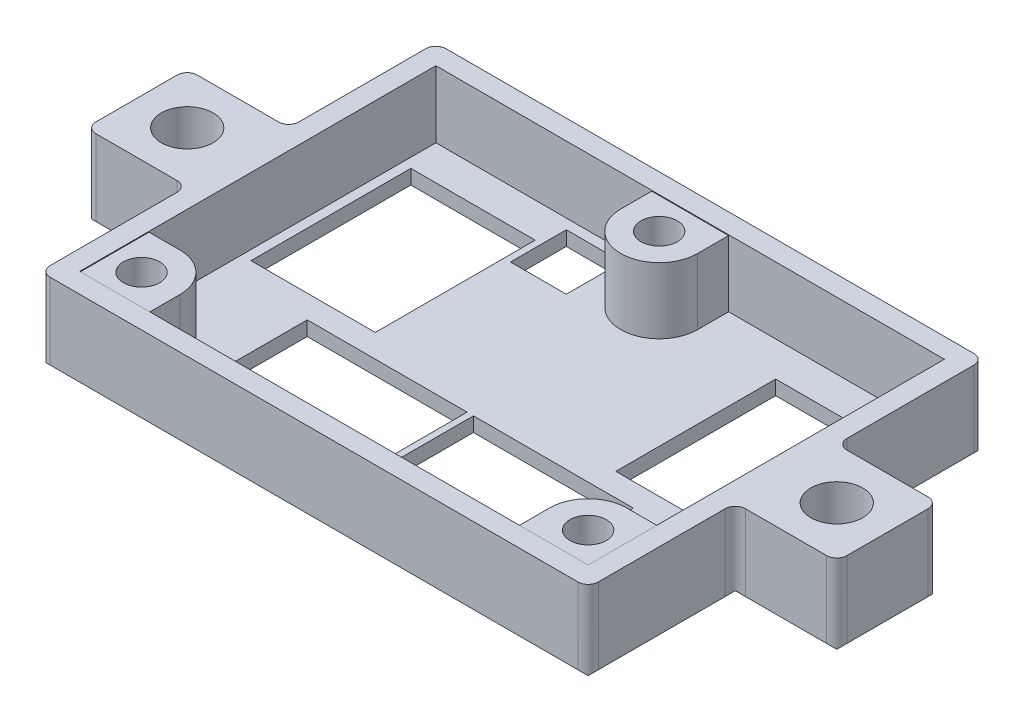
SolidWorks part; units mm, degrees
ref_plane "Front Plane" through (0, 0, 0) normal (0, 0, 1) x (1, 0, 0)
ref_plane "Top Plane" through (0, 0, 0) normal (0, 1, 0) x (1, 0, 0)
ref_plane "Right Plane" through (0, 0, 0) normal (1, 0, 0) x (0, 0, -1)
sketch "Sketch1" plane through (0, 0, 0) normal (0, 1, 0) x (1, 0, 0)
  line L0 (-41.1458, 0) -> (37.3326, 0) construction
  line L1 (-27, -19.5) -> (27, -19.5)
  line L2 (-27, -19.5) -> (-27, 19.5)
  line L3 (-27, 19.5) -> (27, 19.5)
  line L4 (27, -19.5) -> (27, 19.5)
  line L5 (-27, -19.5) -> (27, 19.5) construction
  line L6 (-27, 19.5) -> (27, -19.5) construction
  line L7 (0, 33.589) -> (0, -25.3286) construction
  line L8 (-37, -5) -> (-27, -5)
  line L9 (-37, -5) -> (-37, 5)
  line L10 (-37, 5) -> (-27, 5)
  line L11 (-27, -5) -> (-27, 5)
  line L12 (-37, -5) -> (-27, 5) construction
  line L13 (-37, 5) -> (-27, -5) construction
  line L14 (37, -5) -> (37, 5)
  line L15 (37, 5) -> (27, 5)
  line L16 (37, -5) -> (27, -5)
  circle A0 centre (-32, 0) radius 2.5527
  circle A1 centre (32, 0) radius 2.5527
  point P0 (0, 0)
  point P8 (-32, 0)
  dimension "D5" = 5.1054
  dimension "D1" = 54
  dimension "D2" = 39
  dimension "D3" = 10
  dimension "D4" = 10
extrude "Boss-Extrude1" add sketch "Sketch1" along normal blind 8 contours L1 L4 L3 L2 | L16 L14 L15 L4 A1 | L10 L9 L8 L2 A0
sketch "Sketch2" plane through (0, 8, 0) normal (0, 1, 0) x (1, 0, 0)
  line L0 (0, 27.4) -> (0, -30.8783) construction
  line L1 (-42.9811, 0) -> (41.0645, 0) construction
  line L3 (-25.05, -17.55) -> (25.05, -17.55)
  line L4 (-25.05, -17.55) -> (-25.05, 17.55)
  line L5 (-25.05, 17.55) -> (25.05, 17.55)
  line L6 (25.05, -17.55) -> (25.05, 17.55)
  line L7 (-25.05, -17.55) -> (25.05, 17.55) construction
  line L8 (-25.05, 17.55) -> (25.05, -17.55) construction
  point P5 (0, 0)
  dimension "D1" = 50.1
  dimension "D2" = 35.1
extrude "Cut-Extrude1" cut sketch "Sketch2" against normal blind 0.0762
sketch "Sketch3" plane through (0, 7.9238, 0) normal (0, 1, 0) x (1, 0, 0)
  line L0 (0, 25.6254) -> (0, -24.9156) construction
  line L1 (-43.478, 0) -> (41.2775, 0) construction
  line L2 (-5.4043, 14.5) -> (7.1001, 14.5) construction
  line L3 (-3.79, 14.5) -> (-3.79, 17.55)
  line L4 (25.05, 17.55) -> (-25.05, 17.55) construction
  line L5 (3.79, 14.5) -> (3.79, 17.55)
  line L7 (-22, -6.9215) -> (-22, -24.9156) construction
  line L8 (-15.6235, -14.5) -> (-28.7086, -14.5) construction
  line L9 (-18.21, -14.5) -> (-18.21, -17.55)
  line L10 (-25.05, -17.55) -> (25.05, -17.55) construction
  line L11 (-22, -10.71) -> (-25.05, -10.71)
  line L12 (-25.05, 17.55) -> (-25.05, -17.55) construction
  line L13 (-18.21, -17.55) -> (18.21, -17.55)
  line L14 (-25.05, -10.71) -> (-25.05, 17.55)
  line L15 (-25.05, 17.55) -> (-3.79, 17.55)
  line L16 (18.21, -14.5) -> (18.21, -17.55)
  line L17 (22, -10.71) -> (25.05, -10.71)
  line L18 (25.05, -10.71) -> (25.05, 17.55)
  line L19 (25.05, 17.55) -> (3.79, 17.55)
  arc A0 (-3.79, 14.5) -> (3.79, 14.5) centre (0, 14.5) ccw
  arc A1 (-18.21, -14.5) -> (-22, -10.71) centre (-22, -14.5) ccw
  arc A2 (18.21, -14.5) -> (22, -10.71) centre (22, -14.5) cw
  point P31 (0, -17.55)
  dimension "D1" = 7.58
  dimension "D3" = 7.58
  dimension "D2" = 14.5
  dimension "D4" = 22
  dimension "D5" = 14.5
extrude "Cut-Extrude2" cut sketch "Sketch3" against normal blind 6.5
sketch "Sketch4" plane through (0, 7.9238, 0) normal (0, 1, 0) x (1, 0, 0)
  line L0 (0, 26.0262) -> (0, -25.2956) construction
  line L1 (-42.2713, 0) -> (43.691, 0) construction
  circle A0 centre (0, 14.5) radius 1.56
  circle A1 centre (-22, -14.5) radius 1.56
  circle A2 centre (22, -14.5) radius 1.56
  dimension "D1" = 3.12
  dimension "D2" = 14.5
  dimension "D3" = 22
  dimension "D4" = 14.5
extrude "Cut-Extrude3" cut sketch "Sketch4" against normal through all
sketch "Sketch5" plane through (0, 7.9238, 0) normal (0, 1, 0) x (1, 0, 0)
  line L0 (0, 25.6254) -> (0, -24.7736) construction
  line L1 (-41.9164, 0) -> (40.1417, 0) construction
  circle A0 centre (0, 14.5) radius 1.79
  circle A1 centre (-22, -14.5) radius 1.79
  circle A2 centre (22, -14.5) radius 1.79
  dimension "D1" = 3.58
extrude "Cut-Extrude4" cut sketch "Sketch5" against normal blind 2.92
sketch "Sketch6" plane through (0, 1.4238, 0) normal (0, 1, 0) x (1, 0, 0)
  line L0 (25.05, -17.55) -> (25.05, 17.55) construction
  line L1 (24.1, 14.13) -> (11.85, 14.13)
  line L2 (24.1, 14.13) -> (24.1, -1.62)
  line L3 (24.1, -1.62) -> (11.85, -1.62)
  line L4 (11.85, 14.13) -> (11.85, -1.62)
  line L5 (25.05, 17.55) -> (-25.05, 17.55) construction
  line L6 (-18.21, -17.55) -> (18.21, -17.55) construction
  line L7 (15.85, -3.9) -> (0.1, -3.9)
  line L8 (15.85, -3.9) -> (15.85, -16.4)
  line L9 (15.85, -16.4) -> (0.1, -16.4)
  line L10 (0.1, -3.9) -> (0.1, -16.4)
  line L11 (25.05, -17.55) -> (25.05, -10.71) construction
  line L12 (0, 23.4777) -> (0, -37.1578) construction
  line L13 (-11.85, 14.13) -> (-11.85, -1.62)
  line L14 (-24.1, -1.62) -> (-11.85, -1.62)
  line L15 (-24.1, 14.13) -> (-24.1, -1.62)
  line L16 (-24.1, 14.13) -> (-11.85, 14.13)
  line L17 (-3.79, 17.55) -> (-25.05, 17.55) construction
  line L18 (-0.525, -3.9) -> (-16.275, -3.9)
  line L19 (-0.525, -3.9) -> (-0.525, -16.4)
  line L20 (-0.525, -16.4) -> (-16.275, -16.4)
  line L21 (-16.275, -3.9) -> (-16.275, -16.4)
  line L22 (-11.2, 16.55) -> (-5.7, 16.55)
  line L23 (-11.2, 16.55) -> (-11.2, 11.05)
  line L24 (-11.2, 11.05) -> (-5.7, 11.05)
  line L25 (-5.7, 16.55) -> (-5.7, 11.05)
  dimension "D1" = 0.95
  dimension "D2" = 12.25
  dimension "D3" = 15.75
  dimension "D4" = 3.42
  dimension "D5" = 12.5
  dimension "D6" = 15.75
  dimension "D7" = 1.15
  dimension "D8" = 9.2
  dimension "D9" = 0.625
  dimension "D10" = 12.5
  dimension "D11" = 15.75
  dimension "D12" = 5.5
  dimension "D13" = 5.5
  dimension "D14" = 1
  dimension ".65" = 0.65
extrude "Cut-Extrude5" cut sketch "Sketch6" against normal through all
chamfer "Chamfer1" distance 0.5 angle 45 12 edges at (27, 0, -12.25) (27, 0, 12.25) (0, 0, 19.5) (-27, 0, 12.25) (0, 0, -19.5) (-27, 0, -12.25) (32, 0, -5) (37, 0, 0) (32, 0, 5) (-32, 0, 5) (-32, 0, -5) (-37, 0, 0)
fillet "Fillet1" radius 1 12 edges at (-27, 4.25, -5) (-37, 4.25, 5) (-37, 4.25, -5) (-27, 4.25, 5) (-27, 4.25, 19.5) (27, 4.25, 5) (27, 4.25, 19.5) (-27, 4.25, -19.5) (37, 4.25, 5) (37, 4.25, -5) (27, 4.25, -5) (27, 4.25, -19.5)
